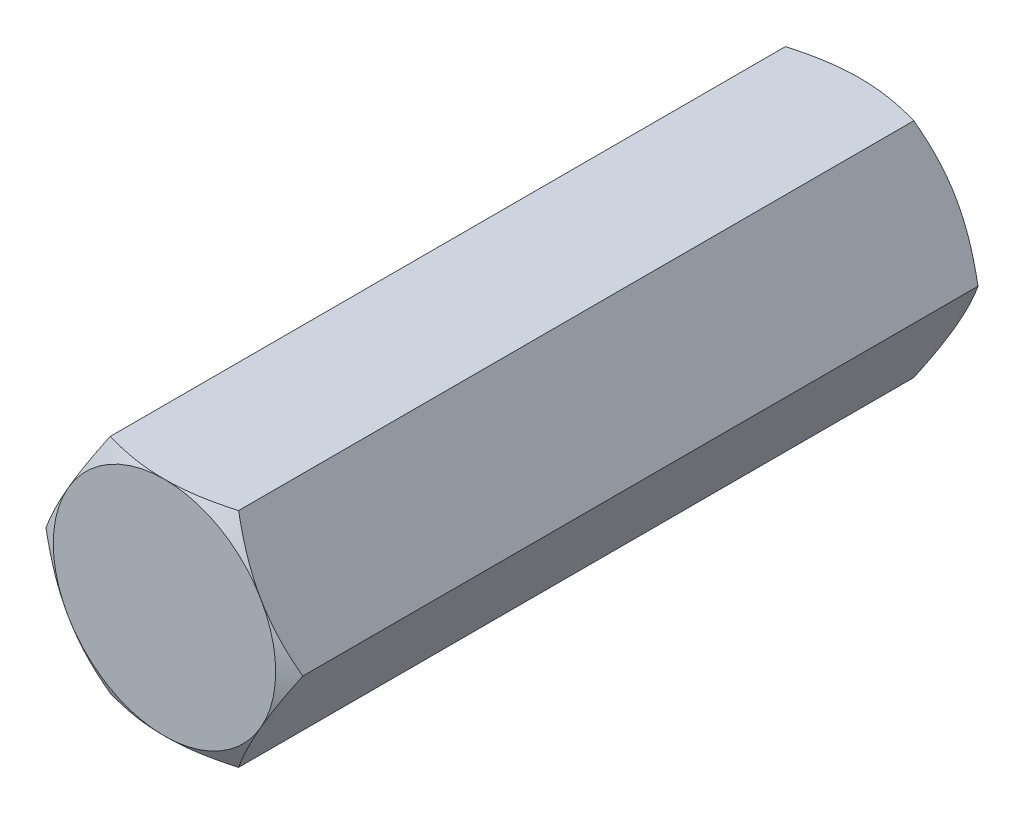
SolidWorks part; units mm, degrees
ref_plane "Front Plane" through (0, 0, 0) normal (0, 0, 1) x (1, 0, 0)
ref_plane "Top Plane" through (0, 0, 0) normal (0, 1, 0) x (1, 0, 0)
ref_plane "Right Plane" through (0, 0, 0) normal (1, 0, 0) x (0, 0, -1)
sketch "Sketch1" plane through (0, 0, 0) normal (0, 0, 1) x (1, 0, 0)
  line L1 (18.4752, 0) -> (9.2376, 16)
  line L2 (9.2376, 16) -> (-9.2376, 16)
  line L3 (-9.2376, 16) -> (-18.4752, 0)
  line L4 (-18.4752, 0) -> (-9.2376, -16)
  line L5 (-9.2376, -16) -> (9.2376, -16)
  line L6 (9.2376, -16) -> (18.4752, 0)
  circle A0 centre (0, 0) radius 16 construction
  dimension "D1" = 32
extrude "Boss-Extrude1" add sketch "Sketch1" along normal blind 100
sketch "Sketch2" plane through (0, 0, 0) normal (1, 0, 0) x (0, 0, -1)
  line L0 (0, 0) -> (-100, 0) construction
  line L1 (-100, 16) -> (-100, 22.8847)
  line L2 (-100, 22.8847) -> (-96.0251, 22.8847)
  line L3 (-96.0251, 22.8847) -> (-100, 16)
  line L4 (-50, 0) -> (-50, 38.246) construction
  line L5 (0, 22.8847) -> (-3.9749, 22.8847)
  line L6 (0, 16) -> (0, 22.8847)
  line L7 (-3.9749, 22.8847) -> (0, 16)
  dimension "D1" = 30
revolve "Cut-Revolve1" cut sketch "Sketch2" angle 360 about L0
